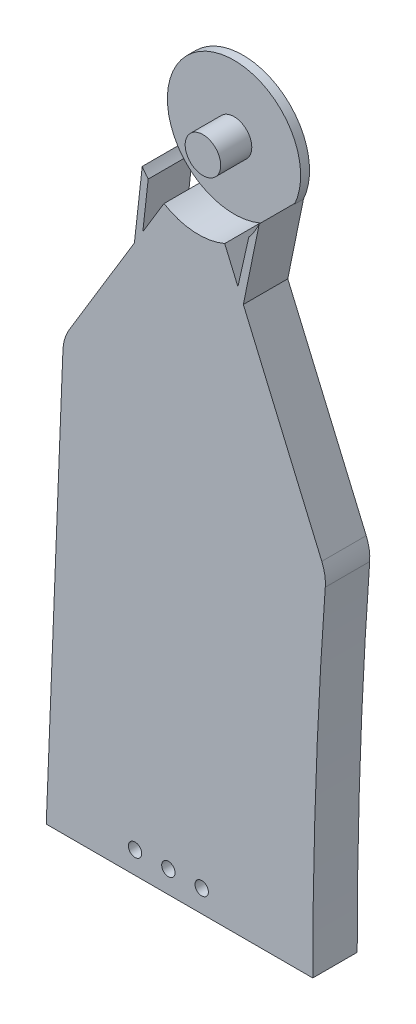
SolidWorks part; units mm, degrees
ref_plane "Front Plane" through (0, 0, 0) normal (0, 0, 1) x (1, 0, 0)
ref_plane "Top Plane" through (0, 0, 0) normal (0, 1, 0) x (1, 0, 0)
ref_plane "Right Plane" through (0, 0, 0) normal (1, 0, 0) x (0, 0, -1)
sketch "Sketch2" plane through (0, 0, 0) normal (0, 0, 1) x (1, 0, 0)
  line L0 (0, 0) -> (70, 0)
  line L1 (110, 290) -> (50, 290)
  arc A0 (70, 0) -> (110, 290) centre (1141.25, 0) cw
  arc A1 (0, 0) -> (50, 290) centre (866, 0) cw
  arc A2 (80, 290) -> (35, 0) centre (845.8662, 22.6673) ccw construction
  dimension "D3" = 40
  dimension "D4" = 290
  dimension "D1" = 70
  dimension "D2" = 60
extrude "Boss-Extrude1" add sketch "Sketch2" along normal blind 10
sketch "Sketch5" plane through (0, 0, 10) normal (0, 0, 1) x (1, 0, 0)
  line L0 (-13.1677, 80) -> (152.8339, 80)
  line L1 (152.8339, 80) -> (152.8339, 337.0509)
  line L2 (152.8339, 337.0509) -> (18.9769, 332.0547)
  line L3 (18.9769, 332.0547) -> (-13.1677, 80)
  line L4 (0, 0) -> (70, 0) construction
  dimension "D1" = 80
extrude "Cut-Extrude2" cut sketch "Sketch5" against normal up to surface (10 mm away) up to face at (51.9097, 145.8781, 0)
sketch "Sketch6" plane through (0, 0, 10) normal (0, 0, 1) x (1, 0, 0)
  line L2 (72.9913, 80) -> (3.7031, 80)
  line L3 (44.2764, 147.0519) -> (3.7031, 80)
  line L4 (44.2764, 147.0519) -> (72.9913, 80)
  arc A1 (80, 290) -> (35, 0) centre (845.8662, 22.6673) ccw construction
extrude "Boss-Extrude2" add sketch "Sketch6" against normal up to surface (10 mm away) up to face at (36.2554, 40.0177, 0)
sketch "Sketch7" plane through (0, 0, 0) normal (0, 0, -1) x (-1, 0, 0)
  circle A1 centre (-44.2764, 147.0519) radius 15
  dimension "D1" = 30
extrude "Cut-Extrude3" cut sketch "Sketch7" against normal blind 17
sketch "Sketch8" plane through (0, 0, 0) normal (0, 0, -1) x (-1, 0, 0)
  circle A1 centre (-44.2764, 147.0519) radius 15
  arc A2 (-35, 0) -> (-80, 290) centre (-845.8662, 22.6673) ccw construction
  dimension "D1" = 30
extrude "Boss-Extrude4" add sketch "Sketch8" against normal blind 2 separate body
sketch "Sketch10" plane through (0, 0, 2) normal (0, 0, 1) x (1, 0, 0)
  circle A1 centre (44.2764, 147.0519) radius 4
  arc A2 (80, 290) -> (35, 0) centre (845.8662, 22.6673) ccw construction
  dimension "D1" = 8
extrude "Boss-Extrude5" add sketch "Sketch10" along normal blind 7
fillet "Fillet1" radius 10 2 edges at (3.7031, 80, 5) (72.9913, 80, 5)
sketch "Sketch11" plane through (0, 0, 10) normal (0, 0, 1) x (1, 0, 0)
  line L0 (13.8659, 96.7952) -> (9.5252, -12.112)
  line L1 (36.5108, 134.2185) -> (4.8961, 81.9716) construction
  line L2 (9.5252, -12.112) -> (-19.8297, -10.942)
  line L3 (-19.8297, -10.942) -> (-15.5357, 96.7952)
  line L4 (-15.5357, 96.7952) -> (13.8659, 96.7952)
  dimension "D1" = 10
extrude "Cut-Extrude4" cut sketch "Sketch11" against normal blind 10
fillet "Fillet2" radius 10 1 edges at (13.8659, 96.7952, 5)
sketch "Sketch12" plane through (0, 0, 0) normal (0, 0, -1) x (-1, 0, 0)
  line L0 (-10.0079, 0) -> (-70, 0) construction
  line L2 (-50, 0) -> (-25, 0)
  line L3 (-50, 0) -> (-50, 10)
  line L4 (-50, 10) -> (-25, 10)
  line L5 (-25, 0) -> (-25, 10)
  line L6 (-70, 0) -> (-70, 36.403) construction
  dimension "D1" = 20
  dimension "25" = 25
  dimension "D2" = 10
extrude "Cut-Extrude5" cut sketch "Sketch12" against normal blind 5
sketch "Sketch13" plane through (0, 0, 5) normal (0, 0, -1) x (-1, 0, 0)
  line L0 (-50, 10) -> (-50, 0) construction
  circle A0 centre (-45, 5) radius 1.505
  circle A1 centre (-37.5, 5) radius 1.505
  circle A2 centre (-30, 5) radius 1.505
  dimension "D1" = 3.01
  dimension "D2" = 7.5
  dimension "D3" = 7.5
  dimension "D4" = 5
extrude "Cut-Extrude6" cut sketch "Sketch13" against normal blind 15
sketch "Sketch14" plane through (0, 0, 0) normal (0, 0, -1) x (-1, 0, 0)
  line L0 (-32.954, 137.213) -> (-31.7423, 126.3379)
  line L2 (-36.5108, 134.2185) -> (-15.1997, 98.9995) construction
  line L3 (-29.8522, 123.2145) -> (-31.7423, 126.3379)
  line L4 (-29.8522, 123.2145) -> (-29.4871, 123.5268)
  line L5 (-29.8522, 123.2145) -> (-31.6126, 139.0128)
  line L6 (-55.5987, 137.213) -> (-53.1471, 126.3379)
  line L7 (-72.0317, 82.241) -> (-50.1814, 133.2632) construction
  line L8 (-53.1471, 126.3379) -> (-54.3729, 123.4756)
  line L9 (-57.9467, 140.9794) -> (-54.3729, 123.4756)
  circle A1 centre (-44.2764, 147.0519) radius 15 construction
  arc A2 (-32.954, 137.213) -> (-31.6126, 139.0128) centre (-44.2764, 147.0519) ccw
  arc A3 (-57.9467, 140.9794) -> (-55.5987, 137.213) centre (-44.1903, 146.9402) ccw
  line M7 (-15.1997, 98.9995) -> (-36.5108, 134.2185)
  line M9 (-50.1814, 133.2632) -> (-72.0317, 82.241)
extrude "Boss-Extrude6" add sketch "Sketch14" against normal blind 10 contours A3 L9 L6 M9 | A2 L0 L5 M7
